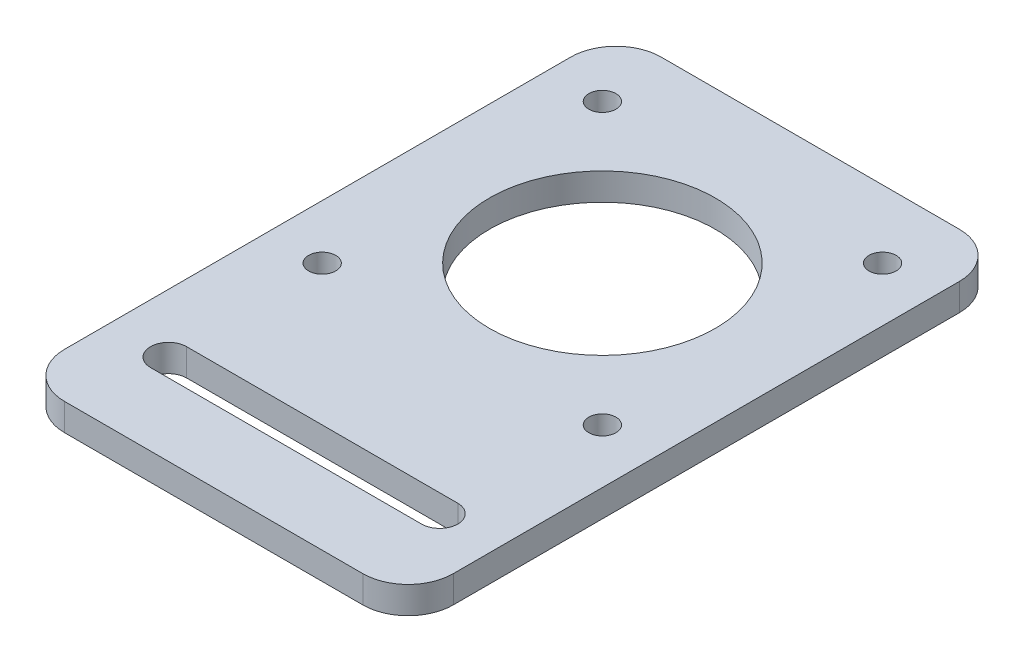
SolidWorks part; units mm, degrees
ref_plane "Front Plane" through (0, 0, 0) normal (0, 0, 1) x (1, 0, 0)
ref_plane "Top Plane" through (0, 0, 0) normal (0, 1, 0) x (1, 0, 0)
ref_plane "Right Plane" through (0, 0, 0) normal (1, 0, 0) x (0, 0, -1)
sketch "Sketch1" plane through (0, 0, 0) normal (0, 1, 0) x (1, 0, 0)
  line L1 (21.5, 33) -> (-21.5, 33)
  line L2 (21.5, 33) -> (21.5, -33)
  line L3 (21.5, -33) -> (-21.5, -33)
  line L4 (-21.5, 33) -> (-21.5, -33)
  line L5 (21.5, 33) -> (-21.5, -33) construction
  line L6 (21.5, -33) -> (-21.5, 33) construction
  point P0 (0, 0)
  dimension "D1" = 43
  dimension "D2" = 66
extrude "Boss-Extrude1" add sketch "Sketch1" along normal blind 3
sketch "Sketch2" plane through (0, 3, 0) normal (0, 1, 0) x (1, 0, 0)
  line L0 (21.5, 33) -> (-21.5, 33) construction
  line L1 (-1001.5607, -23) -> (48998.4393, -23) construction
  line L2 (-1001.5607, -33) -> (48998.4393, -33) construction
  line L3 (-15.5, 25.5) -> (15.5, 25.5) construction
  line L4 (-15.5, 25.5) -> (-15.5, -5.5) construction
  line L5 (-15.5, -5.5) -> (15.5, -5.5) construction
  line L6 (15.5, 25.5) -> (15.5, -5.5) construction
  line L7 (-15.5, 25.5) -> (15.5, -5.5) construction
  line L8 (-15.5, -5.5) -> (15.5, 25.5) construction
  line L9 (-1001.5607, -13) -> (48998.4393, -13) construction
  line L10 (-21.5, -33) -> (21.5, -33) construction
  line L11 (0, -1000) -> (0, 49000) construction
  line L12 (-15, -23) -> (15, -23) construction
  line L13 (-15, -21) -> (15, -21)
  line L14 (-15, -25) -> (15, -25)
  arc A0 (-15, -21) -> (-15, -25) centre (-15, -23) ccw
  arc A1 (15, -25) -> (15, -21) centre (15, -23) ccw
  circle A2 centre (15.5, 25.5) radius 1.5
  circle A3 centre (-15.5, 25.5) radius 1.5
  circle A4 centre (-15.5, -5.5) radius 1.5
  circle A5 centre (15.5, -5.5) radius 1.5
  circle A6 centre (0, 10) radius 12.5
  point P2 (0, 33)
  point P4 (0, 10)
  point P22 (0, -23)
  dimension "D4" = 2
  dimension "D6" = 3
  dimension "D8" = 25
  dimension "D1" = 31
  dimension "D5" = 30
  dimension "D7" = 23
  dimension "D2" = 10
  dimension "D3" = 10
extrude "Cut-Extrude1" cut sketch "Sketch2" against normal through all
fillet "Fillet1" radius 5 4 edges at (21.5, 1.5, 33) (-21.5, 1.5, 33) (-21.5, 1.5, -33) (21.5, 1.5, -33)
